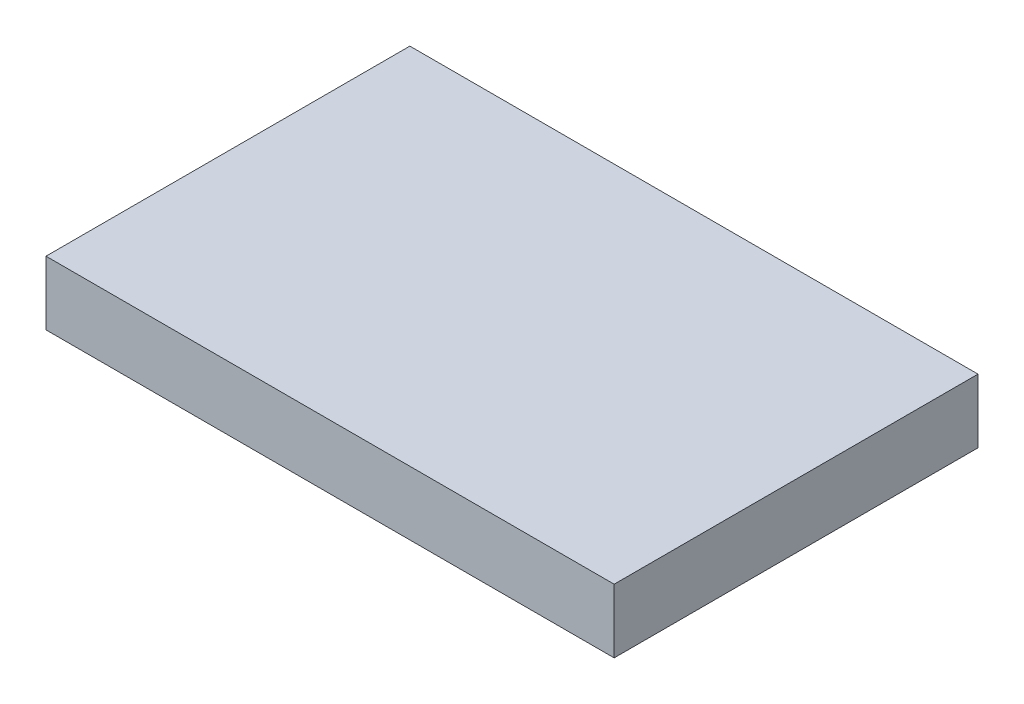
SolidWorks part; units mm, degrees
ref_plane "Front Plane" through (0, 0, 0) normal (0, 0, 1) x (1, 0, 0)
ref_plane "Top Plane" through (0, 0, 0) normal (0, 1, 0) x (1, 0, 0)
ref_plane "Right Plane" through (0, 0, 0) normal (1, 0, 0) x (0, 0, -1)
sketch "Sketch1" plane through (0, 0, 0) normal (0, 1, 0) x (1, 0, 0)
  line L1 (-49.0317, 30.8497) -> (39.9683, 30.8497)
  line L2 (-49.0317, 30.8497) -> (-49.0317, -26.1503)
  line L3 (-49.0317, -26.1503) -> (39.9683, -26.1503)
  line L4 (39.9683, 30.8497) -> (39.9683, -26.1503)
  dimension "D1" = 89
  dimension "D2" = 57
extrude "Boss-Extrude1" add sketch "Sketch1" along normal blind 10
